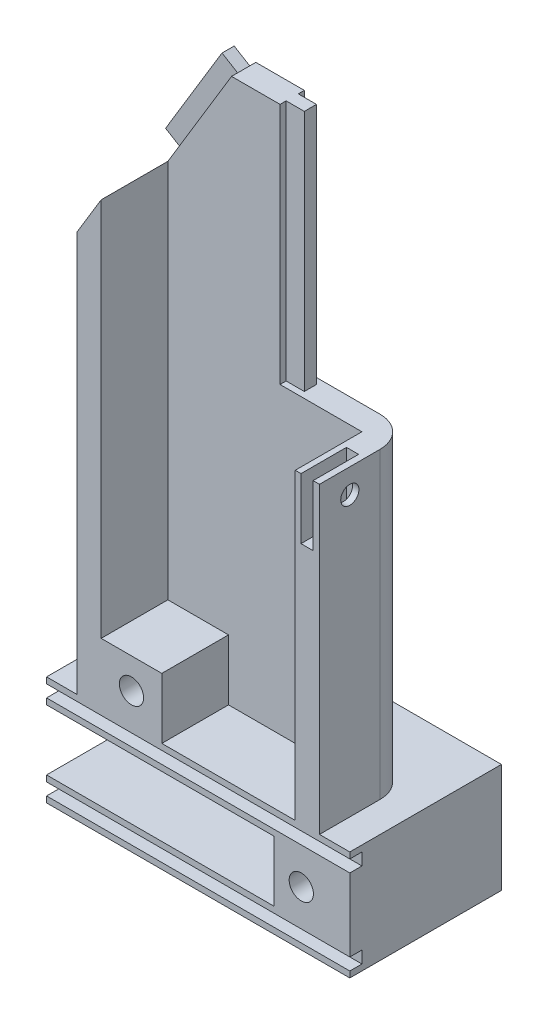
SolidWorks part; units mm, degrees
ref_plane "Front Plane" through (0, 0, 0) normal (0, 0, 1) x (1, 0, 0)
ref_plane "Top Plane" through (0, 0, 0) normal (0, 1, 0) x (1, 0, 0)
ref_plane "Right Plane" through (0, 0, 0) normal (1, 0, 0) x (0, 0, -1)
sketch "Sketch1" plane through (0, 0, 0) normal (0, 1, 0) x (1, 0, 0)
  line L1 (-20, -15) -> (20, -15)
  line L2 (-20, -15) -> (-20, 15)
  line L3 (-20, 15) -> (20, 15)
  line L4 (20, -15) -> (20, 15)
  line L5 (-20, -15) -> (20, 15) construction
  line L6 (-20, 15) -> (20, -15) construction
  point P0 (0, 0)
  dimension "D1" = 40
  dimension "D2" = 30
extrude "Boss-Extrude1" add sketch "Sketch1" along normal blind 90
shell "Shell1" thickness 4
fillet "Fillet1" radius 5 4 edges at (20, 45, -15) (20, 45, 15) (-20, 45, -15) (-20, 45, 15)
sketch "Sketch2" plane through (0, 0, 0) normal (0, 0, 1) x (1, 0, 0)
  line L0 (-5.5, 90) -> (-20, 66)
  line L1 (16, 90) -> (-16, 90) construction
  line L2 (-20, 90) -> (-20, 0) construction
  line L3 (-20, 66) -> (-20, 90)
  line L4 (-20, 90) -> (-5.5, 90)
  dimension "D1" = 5.5
  dimension "D2" = 66
extrude "Cut-Extrude1" cut sketch "Sketch2" against normal through all both and the other way through all
sketch "Sketch3" plane through (0, 0, 0) normal (0, 0, 1) x (1, 0, 0)
  line L1 (20, 90) -> (2.5, 90)
  line L2 (20, 90) -> (20, 50)
  line L3 (20, 50) -> (2.5, 50)
  line L4 (2.5, 90) -> (2.5, 50)
  dimension "D1" = 40
  dimension "D2" = 17.5
extrude "Cut-Extrude2" cut sketch "Sketch3" against normal through all both and the other way through all
sketch "Sketch5" plane through (2.5, 0, 0) normal (1, 0, 0) x (0, 0, -1)
  line L0 (-13, 90) -> (-13, 50) construction
  line L1 (-11, 90) -> (-15, 90) construction
  line L2 (-11, 50) -> (-15, 50) construction
  line L4 (-14, 90) -> (-12, 90)
  line L5 (-14, 90) -> (-14, 50)
  line L6 (-14, 50) -> (-12, 50)
  line L7 (-12, 90) -> (-12, 50)
  dimension "D1" = 2
extrude "Boss-Extrude2" add sketch "Sketch5" along normal blind 3
mirror "Mirror1" about plane through (0, 0, 0) normal (0, 0, 1) of "Boss-Extrude2"
sketch "Sketch6" plane through (-43.8639, 26.5011, 0) normal (-0.8559, 0.5171, 0) x (0, 0, 1)
  line L0 (-13, 74.1883) -> (-13, 56.1883) construction
  line L1 (-15, 74.1883) -> (-11, 74.1883) construction
  line L3 (-14, 74.1883) -> (-12, 74.1883)
  line L4 (-14, 74.1883) -> (-14, 56.1883)
  line L5 (-14, 56.1883) -> (-12, 56.1883)
  line L6 (-12, 74.1883) -> (-12, 56.1883)
  dimension "D1" = 18
  dimension "D2" = 2
extrude "Boss-Extrude3" add sketch "Sketch6" along normal blind 3
mirror "Mirror2" about plane through (0, 0, 0) normal (0, 0, 1) of "Boss-Extrude3"
sketch "Sketch8" plane through (0, 0, 0) normal (0, 1, 0) x (1, 0, 0)
  line L1 (-25, -25) -> (25, -25)
  line L2 (-25, -25) -> (-25, 25)
  line L3 (-25, 25) -> (25, 25)
  line L4 (25, -25) -> (25, 25)
  line L5 (-25, -25) -> (25, 25) construction
  line L6 (-25, 25) -> (25, -25) construction
  point P0 (0, 0)
  dimension "D1" = 50
  dimension "D2" = 50
extrude "Boss-Extrude4" add sketch "Sketch8" against normal blind 18
sketch "Sketch10" plane through (-25, 0, 0) normal (-1, 0, 0) x (0, 0, 1)
  line L0 (-25, -9) -> (25, -9) construction
  line L1 (-22.5, -14) -> (22.5, -14)
  line L2 (-22.5, -14) -> (-22.5, -4)
  line L3 (-22.5, -4) -> (22.5, -4)
  line L4 (22.5, -14) -> (22.5, -4)
  line L5 (-22.5, -14) -> (22.5, -4) construction
  line L6 (-22.5, -4) -> (22.5, -14) construction
  line L7 (-25, -18) -> (-25, 0) construction
  line L8 (25, -18) -> (25, 0) construction
  line L9 (0, 0) -> (0, -18) construction
  line L10 (-25, -18) -> (25, -18) construction
  point P0 (0, -9)
  dimension "D1" = 45
  dimension "D2" = 10
extrude "Cut-Extrude4" cut sketch "Sketch10" against normal blind 37.5
sketch "Sketch15" plane through (0, 0, -11) normal (0, 0, 1) x (1, 0, 0)
  line L1 (-16, 0) -> (-6, 0)
  line L2 (-16, 0) -> (-16, 10)
  line L3 (-16, 10) -> (-6, 10)
  line L4 (-6, 0) -> (-6, 10)
  dimension "D1" = 10
  dimension "D2" = 10
extrude "Boss-Extrude5" add sketch "Sketch15" along normal up to next
sketch "Sketch20" plane through (0, 0, -15) normal (0, 0, -1) x (-1, 0, 0)
  line L0 (16, 72.6207) -> (16, 10) construction
  line L2 (-16, 0) -> (6, 0) construction
  circle A0 centre (11, 5) radius 2
  dimension "D2" = 5
  dimension "D3" = 4
  dimension "D1" = 5
extrude "Cut-Extrude8" cut sketch "Sketch20" against normal through all both and the other way through all
sketch "Sketch21" plane through (0, 0, -15) normal (0, 0, -1) x (-1, 0, 0)
  circle A0 centre (11, 5) radius 4
  dimension "D1" = 8
extrude "Cut-Extrude9" cut sketch "Sketch21" against normal blind 5
mirror "Mirror3" about plane through (0, 0, 0) normal (0, 0, 1) of "Cut-Extrude9"
sketch "Sketch23" plane through (0, 50, 0) normal (0, 1, 0) x (1, 0, 0)
  line L0 (0, 0) -> (20, 0) construction
  line L1 (16.9495, 7.5) -> (18.9495, 7.5)
  line L2 (16.9495, 7.5) -> (16.9495, -7.5)
  line L3 (16.9495, -7.5) -> (18.9495, -7.5)
  line L4 (18.9495, 7.5) -> (18.9495, -7.5)
  line L5 (20, 10) -> (20, -10) construction
  line L6 (16, 11) -> (19.899, 11) construction
  line L7 (16, -11) -> (19.899, -11) construction
  line L8 (17.9495, 11) -> (17.9495, -11) construction
  arc A0 (20, 10) -> (15, 15) centre (15, 10) ccw construction
  arc A1 (15, -15) -> (20, -10) centre (15, -10) ccw construction
  dimension "D1" = 2
  dimension "D2" = 15
extrude "Cut-Extrude10" cut sketch "Sketch23" against normal blind 10
sketch "Sketch24" plane through (20, 0, 0) normal (1, 0, 0) x (0, 0, -1)
  line L0 (-10, 50) -> (-10, 0) construction
  line L1 (10, 50) -> (-10, 50) construction
  circle A0 centre (-5, 46) radius 1.5
  point P2 (0, 0)
  dimension "D3" = 3
  dimension "D1" = 5
  dimension "D2" = 4
extrude "Cut-Extrude11" cut sketch "Sketch24" against normal blind 10 and the other way through all
mirror "Mirror4" about plane through (0, 0, 0) normal (0, 0, 1) of "Cut-Extrude11"
sketch "Sketch27" plane through (0, 0, 0) normal (0, 1, 0) x (1, 0, 0)
  line L0 (25, -25) -> (25, 25) construction
  line L1 (-25, -25) -> (25, -25)
  line L2 (-25, -25) -> (-25, 0)
  line L3 (-25, 0) -> (25, 0)
  line L4 (25, -25) -> (25, 0)
  point P7 (-25, 25)
  point P8 (25, 25)
  point P9 (-25, -25)
extrude "Cut-Extrude12" cut sketch "Sketch27" against normal through all both and the other way through all
sketch "Sketch29" plane through (0, 0, 0) normal (0, 0, 1) x (1, 0, 0)
  line L0 (-25, -2) -> (25, -2) construction
  line L1 (-25, -4) -> (-25, 0) construction
  line L2 (25, -18) -> (25, 0) construction
  line L3 (-25, -1) -> (25, -1)
  line L4 (-25, -1) -> (-25, -3)
  line L5 (-25, -3) -> (25, -3)
  line L6 (25, -1) -> (25, -3)
  point P8 (-25, -3)
  point P11 (-25, -2)
  dimension "D1" = 2
extrude "Cut-Extrude13" cut sketch "Sketch29" against normal blind 2
sketch "Sketch30" plane through (0, 0, 0) normal (0, 0, 1) x (1, 0, 0)
  line L0 (-25, -16) -> (25, -16) construction
  line L1 (-25, -18) -> (-25, -14) construction
  line L2 (25, -18) -> (25, -3) construction
  line L4 (-25, -15) -> (25, -15)
  line L5 (-25, -15) -> (-25, -17)
  line L6 (-25, -17) -> (25, -17)
  line L7 (25, -15) -> (25, -17)
  point P10 (0, 0)
  point P11 (0, 0)
  dimension "D1" = 2
extrude "Cut-Extrude14" cut sketch "Sketch30" against normal blind 2
sketch "Sketch31" plane through (0, 0, 0) normal (0, 0, 1) x (1, 0, 0)
  line L0 (25, -15) -> (25, -3) construction
  line L1 (25, -18) -> (-25, -18) construction
  circle A0 centre (17, -9) radius 2
  dimension "D1" = 4
  dimension "D2" = 8
  dimension "D3" = 9
extrude "Cut-Extrude15" cut sketch "Sketch31" against normal through all both and the other way through all
sketch "Sketch33" plane through (0, 0, -25) normal (0, 0, -1) x (-1, 0, 0)
  circle A0 centre (-17, -9) radius 4
  dimension "D1" = 8
extrude "Cut-Extrude16" cut sketch "Sketch33" against normal blind 15
